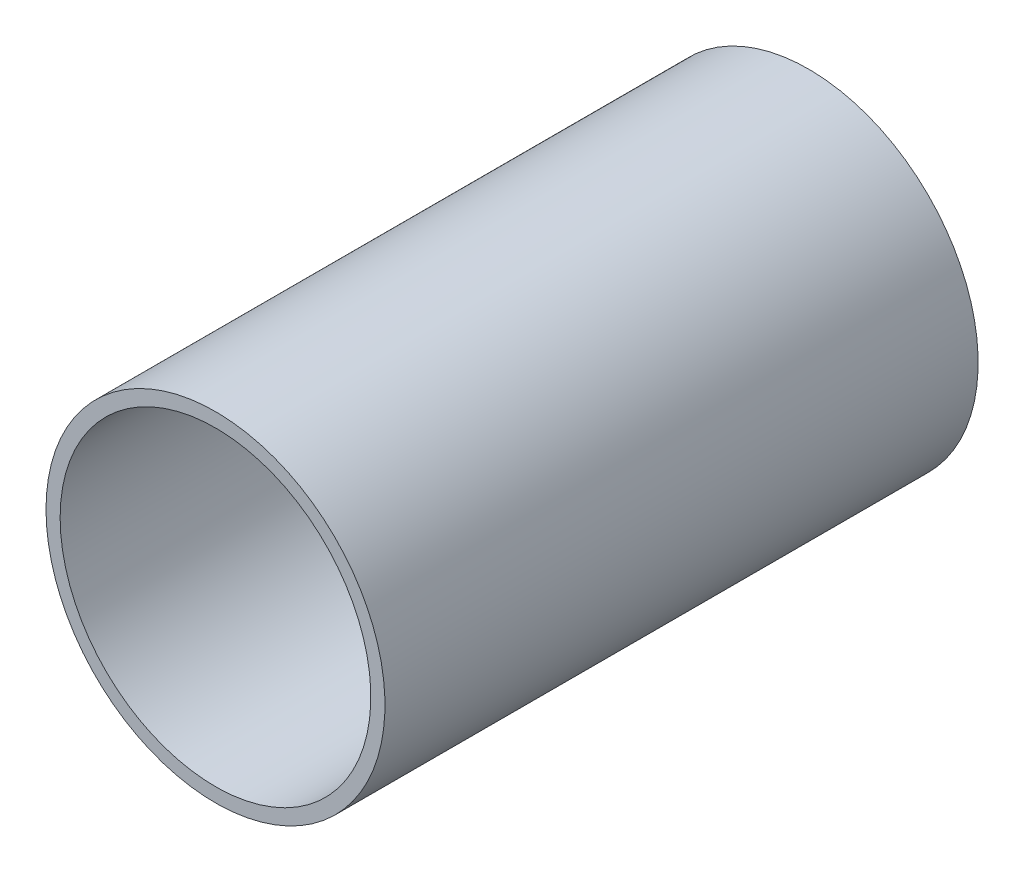
SolidWorks part; units mm, degrees
ref_plane "Front Plane" through (0, 0, 0) normal (0, 0, 1) x (1, 0, 0)
ref_plane "Top Plane" through (0, 0, 0) normal (0, 1, 0) x (1, 0, 0)
ref_plane "Right Plane" through (0, 0, 0) normal (1, 0, 0) x (0, 0, -1)
sketch "Sketch1" plane through (0, 0, 0) normal (0, 0, 1) x (1, 0, 0)
  circle A0 centre (0, 0) radius 11
  circle A1 centre (0, 0) radius 12
  dimension "D1" = 24
  dimension "D2" = 22
extrude "Boss-Extrude1" add sketch "Sketch1" along normal blind 42 contours A1
